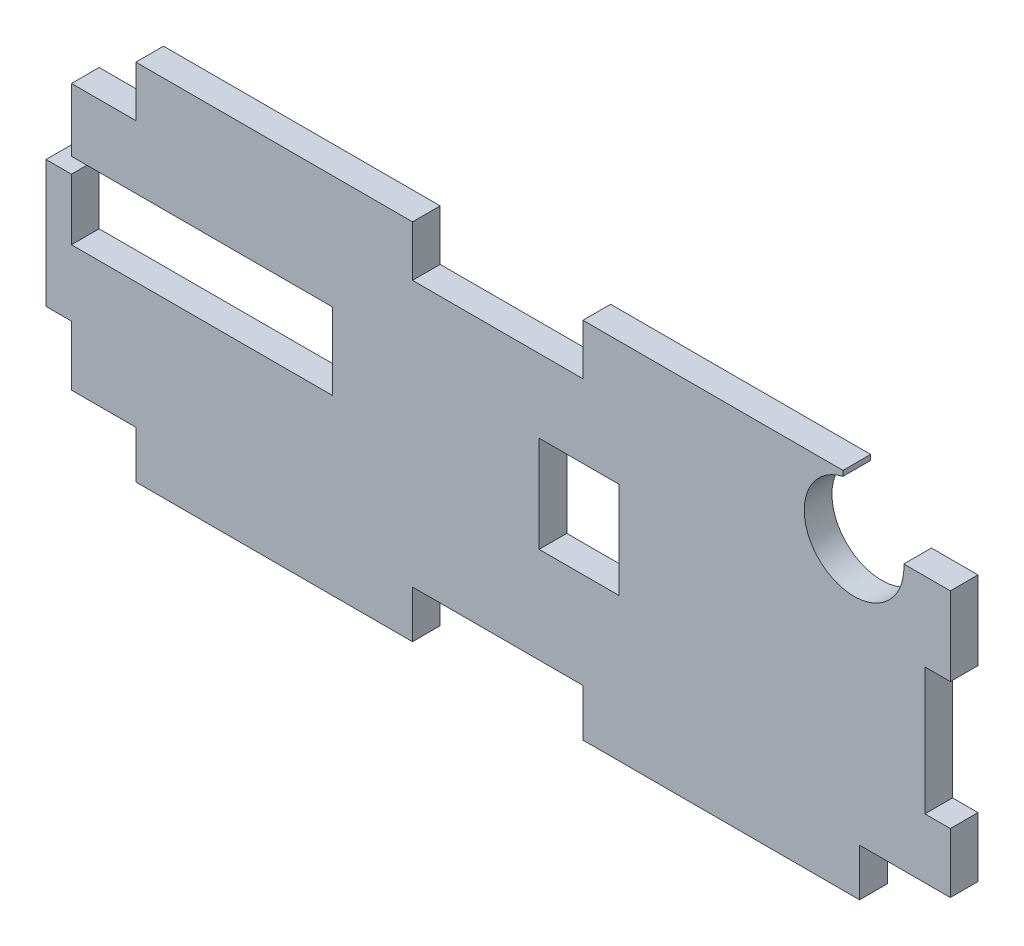
SolidWorks part; units mm, degrees
ref_plane "Front Plane" through (0, 0, 0) normal (0, 0, 1) x (1, 0, 0)
ref_plane "Top Plane" through (0, 0, 0) normal (0, 1, 0) x (1, 0, 0)
ref_plane "Right Plane" through (0, 0, 0) normal (1, 0, 0) x (0, 0, -1)
sketch "Sketch1" plane through (0, 0, 0) normal (0, 0, 1) x (1, 0, 0)
  line L0 (-1000, 0) -> (49000, 0) construction
  line L1 (0, -1000) -> (0, 49000) construction
  line L2 (-51.8414, 0) -> (-51.8414, 7.3152)
  line L3 (-51.8414, 7.3152) -> (-48.9204, 7.3152)
  line L4 (-48.9204, 7.3152) -> (-48.9204, 17.3482)
  line L5 (-48.9204, 17.3482) -> (-41.529, 17.3482)
  line L6 (-41.529, 17.3482) -> (-41.529, 22.7838)
  line L7 (-41.529, 22.7838) -> (-9.779, 22.7838)
  line L8 (-9.779, 22.7838) -> (-9.779, 17.3482)
  line L9 (-9.779, 17.3482) -> (9.779, 17.3482)
  line L10 (9.779, 17.3482) -> (9.779, 22.7838)
  line L11 (9.779, 22.7838) -> (41.529, 22.7838)
  line L12 (41.529, 22.7838) -> (41.529, 17.3482)
  line L13 (41.529, 17.3482) -> (51.943, 17.3482)
  line L14 (51.943, 17.3482) -> (51.943, 7.3152)
  line L15 (51.943, 7.3152) -> (49.022, 7.3152)
  line L16 (49.022, 7.3152) -> (49.022, 0)
  line L17 (-51.8414, 0) -> (-51.8414, -7.2898)
  line L18 (-51.8414, -7.2898) -> (-48.9204, -7.2898)
  line L19 (-48.9204, -7.2898) -> (-48.9204, -14.1478)
  line L20 (-48.9204, -14.1478) -> (-41.529, -14.1478)
  line L21 (-41.529, -14.1478) -> (-41.529, -19.5834)
  line L22 (-41.529, -19.5834) -> (-9.779, -19.5834)
  line L23 (-9.779, -19.5834) -> (-9.779, -14.1478)
  line L24 (-9.779, -14.1478) -> (9.779, -14.1478)
  line L25 (9.779, -14.1478) -> (9.779, -19.5834)
  line L26 (9.779, -19.5834) -> (41.529, -19.5834)
  line L27 (41.529, -19.5834) -> (41.529, -14.1478)
  line L28 (41.529, -14.1478) -> (51.943, -14.1478)
  line L29 (51.943, -14.1478) -> (51.943, -7.2898)
  line L30 (51.943, -7.2898) -> (49.022, -7.2898)
  line L31 (49.022, -7.2898) -> (49.022, 0)
  line L32 (0, -981.7882) -> (0, 49018.2118) construction
  point P38 (0, 17.3482)
  dimension "D1" = 7.3152
  dimension "D2" = 7.2898
  dimension "D3" = 6.858
  dimension "D4" = 10.033
  dimension "D5" = 5.4356
  dimension "D6" = 5.4356
  dimension "D7" = 5.4356
  dimension "D8" = 5.4356
  dimension "D11" = 5.4356
  dimension "D13" = 10.033
  dimension "D14" = 6.858
  dimension "D15" = 19.558
  dimension "D16" = 19.558
  dimension "D17" = 31.75
  dimension "D18" = 31.75
  dimension "D19" = 31.75
  dimension "D20" = 31.75
  dimension "D21" = 7.3914
  dimension "D22" = 7.3914
  dimension "D23" = 2.921
  dimension "D24" = 2.921
  dimension "D25" = 10.414
  dimension "D26" = 10.414
  dimension "D27" = 2.921
extrude "Boss-Extrude1" add sketch "Sketch1" along normal blind 3.175
sketch "Sketch2" plane through (0, 0, 3.175) normal (0, 0, 1) x (1, 0, 0)
  line L0 (-48.9204, 17.3482) -> (-48.9204, 7.3152) construction
  line L1 (-48.9204, 9.0932) -> (-18.9484, 9.0932)
  line L2 (-48.9204, 9.0932) -> (-48.9204, 0.2985)
  line L3 (-48.9204, 0.2985) -> (-18.9484, 0.2985)
  line L4 (-18.9484, 9.0932) -> (-18.9484, 0.2985)
  line L5 (-41.529, 17.3482) -> (-48.9204, 17.3482) construction
  line L6 (49.022, -7.2898) -> (49.022, 7.3152) construction
  line L7 (4.7498, 7.9121) -> (13.8938, 7.9121)
  line L8 (4.7498, 7.9121) -> (4.7498, -3.1369)
  line L9 (4.7498, -3.1369) -> (13.8938, -3.1369)
  line L10 (13.8938, 7.9121) -> (13.8938, -3.1369)
  line L11 (9.779, 17.3482) -> (-9.779, 17.3482) construction
  line L12 (35.179, -984.0234) -> (35.179, 49015.9766) construction
  line L13 (41.529, 17.3482) -> (41.529, 22.7838) construction
  circle A0 centre (40.894, 15.9766) radius 5.715
  dimension "D8" = 11.43
  dimension "D1" = 29.972
  dimension "D2" = 8.7948
  dimension "D3" = 8.255
  dimension "D4" = 9.144
  dimension "D5" = 11.049
  dimension "D6" = 35.1282
  dimension "D7" = 9.4361
  dimension "D9" = 6.35
extrude "Cut-Extrude1" cut sketch "Sketch2" against normal blind 5.4356
sketch "Sketch3" plane through (0, 0, 3.175) normal (0, 0, 1) x (1, 0, 0)
  line L0 (41.529, 22.7838) -> (9.779, 22.7838) construction
  line L1 (41.529, 21.5487) -> (39.624, 21.5487)
  line L2 (41.529, 21.5487) -> (41.529, 22.7838)
  line L3 (41.529, 22.7838) -> (39.624, 22.7838)
  line L4 (39.624, 21.5487) -> (39.624, 22.7838)
  line L5 (41.529, 21.6562) -> (41.529, 22.7838) construction
  arc A0 (41.529, 21.6562) -> (46.442, 17.3482) centre (40.894, 15.9766) ccw construction
  dimension "D1" = 1.905
extrude "Cut-Extrude2" cut sketch "Sketch3" against normal through all
sketch "Sketch4" plane through (0, 0, 3.175) normal (0, 0, 1) x (1, 0, 0)
  line L0 (51.943, 7.3152) -> (51.943, 17.3482) construction
  line L1 (46.442, 17.3482) -> (51.943, 17.3482)
  line L2 (46.442, 17.3482) -> (46.442, 16.3322)
  line L3 (46.442, 16.3322) -> (51.943, 16.3322)
  line L4 (51.943, 17.3482) -> (51.943, 16.3322)
  line L5 (-48.9204, 17.3482) -> (-48.9204, 9.0932) construction
  line L6 (-9.779, 17.3482) -> (9.779, 17.3482)
  line L7 (-9.779, 17.3482) -> (-9.779, 16.3322)
  line L8 (-9.779, 16.3322) -> (9.779, 16.3322)
  line L9 (9.779, 17.3482) -> (9.779, 16.3322)
  line L10 (-41.529, 17.3482) -> (-48.9204, 17.3482)
  line L11 (-41.529, 17.3482) -> (-41.529, 16.3322)
  line L12 (-41.529, 16.3322) -> (-48.9204, 16.3322)
  line L13 (-48.9204, 17.3482) -> (-48.9204, 16.3322)
  line L14 (9.779, 22.7838) -> (9.779, 17.3482) construction
  dimension "D1" = 1.016
extrude "Cut-Extrude3" cut sketch "Sketch4" against normal through all
sketch "Sketch5" plane through (0, 0, 3.175) normal (0, 0, 1) x (1, 0, 0)
  line L0 (-9.779, 16.3322) -> (-9.779, 22.7838) construction
  line L1 (-41.529, 22.7838) -> (-9.779, 22.7838)
  line L2 (-41.529, 22.7838) -> (-41.529, 22.1488)
  line L3 (-41.529, 22.1488) -> (-9.779, 22.1488)
  line L4 (-9.779, 22.7838) -> (-9.779, 22.1488)
  line L5 (39.624, 22.7838) -> (39.624, 21.5487) construction
  line L6 (9.779, 22.7838) -> (39.624, 22.7838)
  line L7 (9.779, 22.7838) -> (9.779, 22.1488)
  line L8 (9.779, 22.1488) -> (39.624, 22.1488)
  line L9 (39.624, 22.7838) -> (39.624, 22.1488)
  dimension "D1" = 0.635
extrude "Cut-Extrude4" cut sketch "Sketch5" against normal through all
